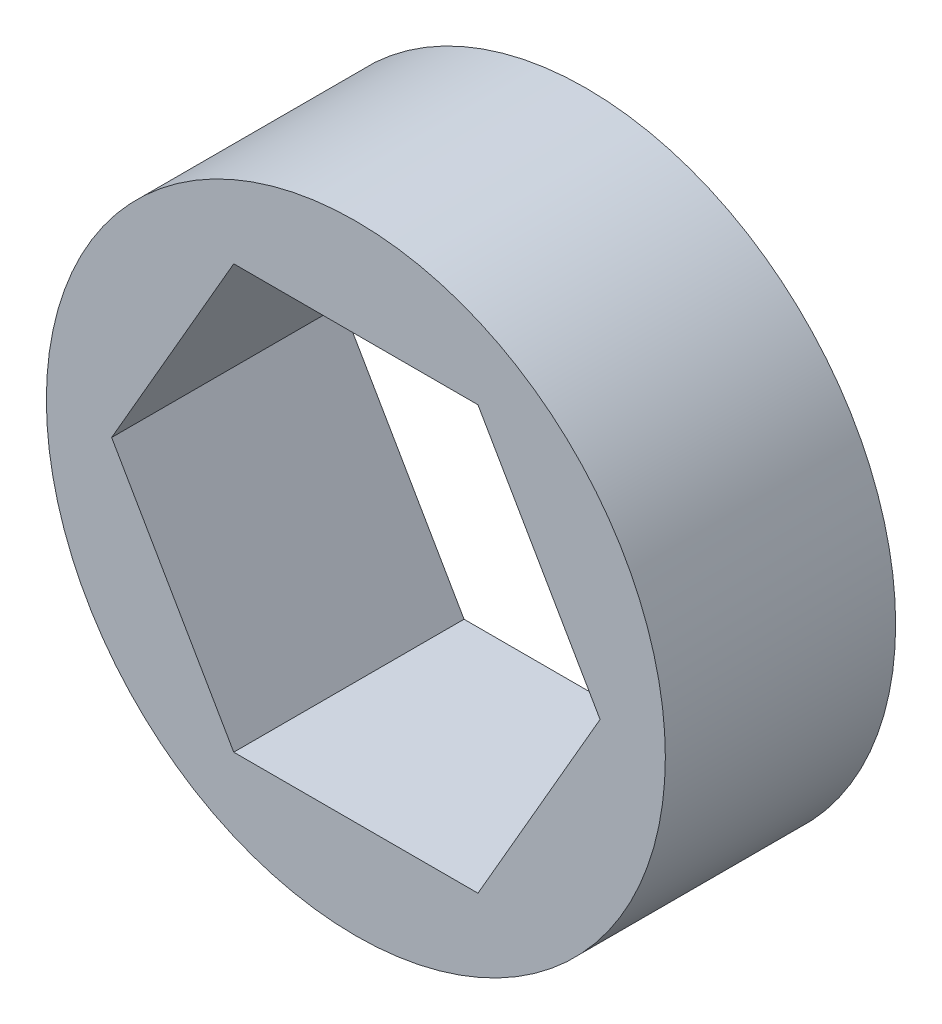
SolidWorks part; units mm, degrees
material "PET"
ref_plane "Front Plane" through (0, 0, 0) normal (0, 0, 1) x (1, 0, 0)
ref_plane "Top Plane" through (0, 0, 0) normal (0, 1, 0) x (1, 0, 0)
ref_plane "Right Plane" through (0, 0, 0) normal (1, 0, 0) x (0, 0, -1)
sketch "Sketch1" plane through (0, 0, 0) normal (0, 0, 1) x (1, 0, 0)
  line L1 (7.5157, 0) -> (3.7578, 6.5087)
  line L2 (3.7578, 6.5087) -> (-3.7578, 6.5087)
  line L3 (-3.7578, 6.5087) -> (-7.5157, 0)
  line L4 (-7.5157, 0) -> (-3.7578, -6.5088)
  line L5 (-3.7578, -6.5088) -> (3.7578, -6.5087)
  line L6 (3.7578, -6.5087) -> (7.5157, 0)
  circle A0 centre (0, 0) radius 6.5087 construction
  circle A1 centre (0, 0) radius 9.525
  dimension "D1" = 13.0175
  dimension "D2" = 19.05
extrude "Boss-Extrude1" add sketch "Sketch1" along normal blind 7.0875
